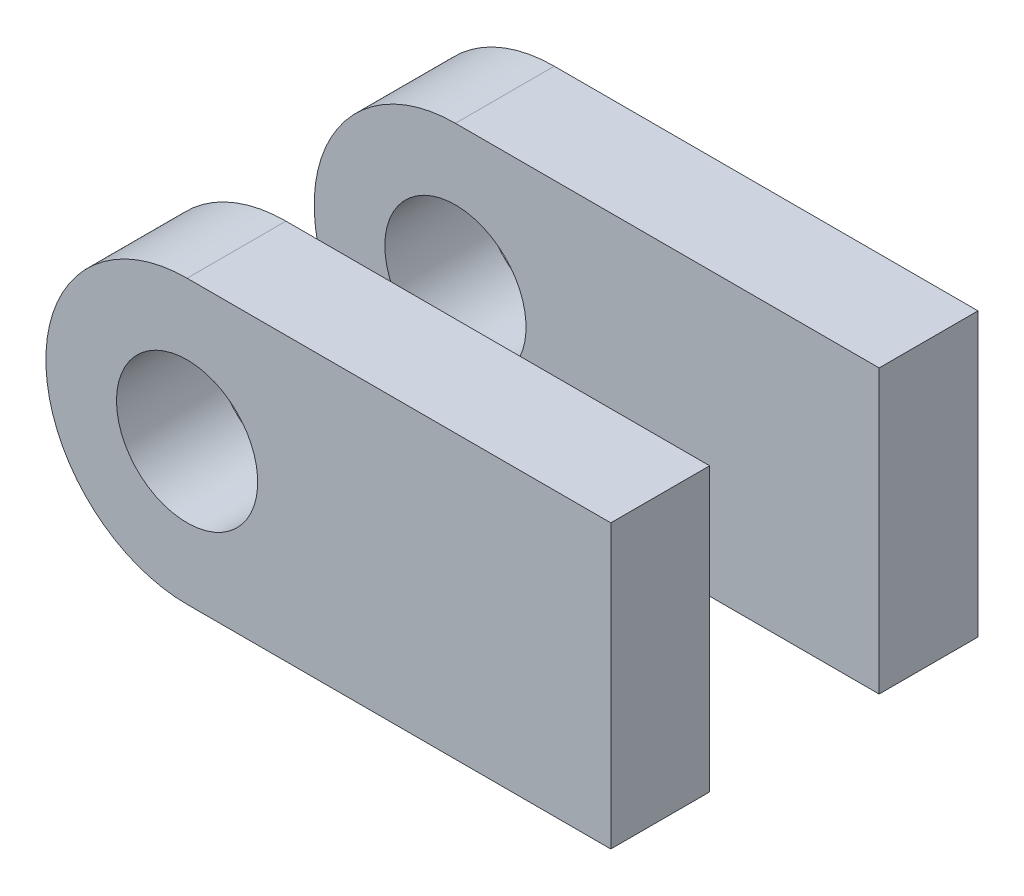
SolidWorks part; units mm, degrees
material "AISI 4130 Steel, normalized at 870C"
ref_plane "Front Plane" through (0, 0, 0) normal (0, 0, 1) x (1, 0, 0)
ref_plane "Top Plane" through (0, 0, 0) normal (0, 1, 0) x (1, 0, 0)
ref_plane "Right Plane" through (0, 0, 0) normal (1, 0, 0) x (0, 0, -1)
sketch "Sketch7" plane through (0, 0, 0) normal (0, 1, 0) x (1, 0, 0)
  line L0 (0, 6) -> (40, 6)
  line L1 (40, 6) -> (40, 13)
  line L2 (40, 13) -> (0, 13)
  line L4 (0, 13) -> (0, 6)
  line L5 (0, -13) -> (40, -13)
  line L6 (40, -13) -> (40, -6)
  line L7 (40, -6) -> (0, -6)
  line L8 (0, -6) -> (0, -13)
  line L9 (0, 6) -> (0, -6) construction
  point P2 (0, 0)
  dimension "D1" = 12
  dimension "D2" = 7
  dimension "D3" = 40
extrude "Boss-Extrude3" add sketch "Sketch7" along normal blind 20
sketch "Sketch8" plane through (0, 0, -13) normal (0, 0, -1) x (-1, 0, 0)
  line L1 (-40, 20) -> (0, 20) construction
  line L2 (-40, 0) -> (0, 0) construction
  line L3 (0, 20) -> (0, 0) construction
  line L6 (-10, 20) -> (6.2691, 20)
  line L7 (6.2691, 20) -> (6.2691, 0)
  line L8 (6.2691, 0) -> (-10, 0)
  arc A0 (-10, 20) -> (-10, 0) centre (-10, 10) cw
  point P9 (0, 10)
  point P12 (0, 10)
extrude "Cut-Extrude9" cut sketch "Sketch8" against normal blind 26
sketch "Sketch9" plane through (0, 0, -13) normal (0, 0, -1) x (-1, 0, 0)
  circle A0 centre (-10, 10) radius 5
  dimension "D1" = 10
extrude "Cut-Extrude10" cut sketch "Sketch9" against normal blind 26
